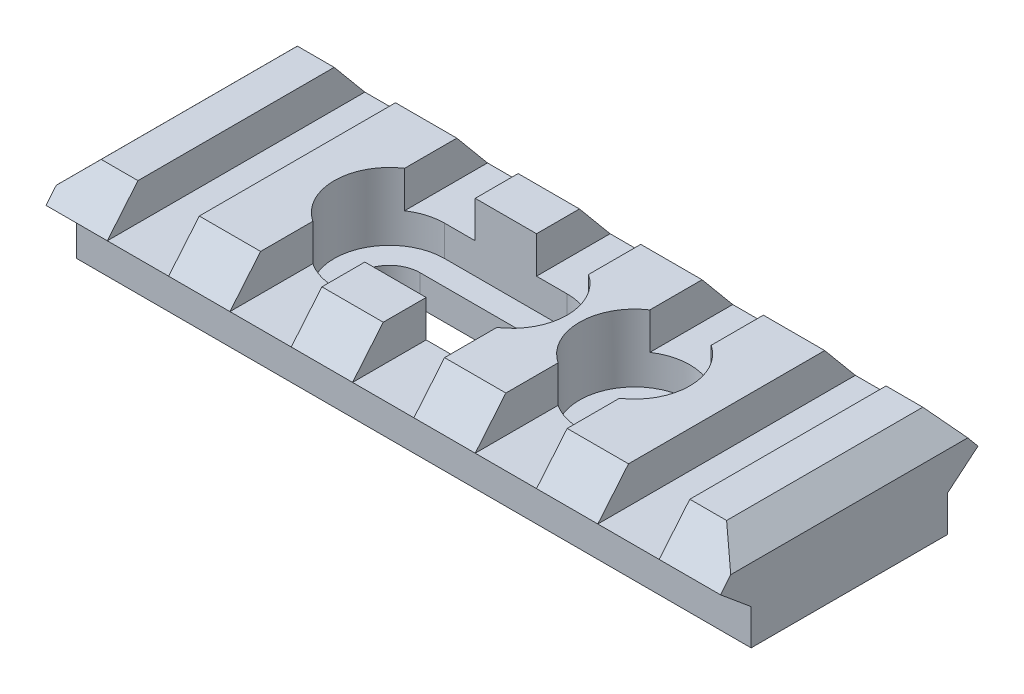
SolidWorks part; units mm, degrees
ref_plane "前视基准面" through (0, 0, 0) normal (0, 0, 1) x (1, 0, 0)
ref_plane "上视基准面" through (0, 0, 0) normal (0, 1, 0) x (1, 0, 0)
ref_plane "右视基准面" through (0, 0, 0) normal (1, 0, 0) x (0, 0, -1)
other "Configuration Table"
sketch "草图1" plane through (0, 0, 0) normal (1, 0, 0) x (0, 0, -1)
  line L0 (-8, 0) -> (8, 0)
  line L1 (8, 0) -> (8, 2.9167)
  line L2 (8, 2.9167) -> (10.5, 5)
  line L3 (10.5, 5) -> (8, 8)
  line L4 (8, 8) -> (-8, 8)
  line L5 (-8, 8) -> (-10.5, 5)
  line L6 (-10.5, 5) -> (-8, 2.9167)
  line L7 (-8, 2.9167) -> (-8, 0)
  line L8 (0, 0) -> (0, 8) construction
  dimension "D1" = 16
  dimension "D2" = 21
  dimension "D3" = 8
  dimension "D4" = 5
  dimension "D5" = 16
extrude "凸台-拉伸1" add sketch "草图1" along normal mid plane 55
sketch "草图2" plane through (0, 8, 0) normal (0, 1, 0) x (1, 0, 0)
  line L0 (27.5, 10.5) -> (-27.5, 10.5) construction
  line L1 (-2.5, -10.5) -> (2.5, -10.5)
  line L2 (-2.5, -10.5) -> (-2.5, 10.5)
  line L3 (-2.5, 10.5) -> (2.5, 10.5)
  line L4 (2.5, -10.5) -> (2.5, 10.5)
  line L5 (-2.5, -10.5) -> (2.5, 10.5) construction
  line L6 (-2.5, 10.5) -> (2.5, -10.5) construction
  point P0 (0, 0)
  dimension "D1" = 5
extrude "切除-拉伸1" cut sketch "草图2" against normal up to vertex (3 mm away) up to point (27.5, 5, 10.5)
pattern_linear "阵列(线性)1" count 3 spacing 10 along (1, 0, 0) of "切除-拉伸1"
pattern_linear "阵列(线性)2" count 3 spacing 10 along (-1, 0, 0) of "阵列(线性)1"
sketch "草图3" plane through (0, 0, 0) normal (0, -1, 0) x (1, 0, 0)
  line L0 (27.5, 8) -> (27.5, -8) construction
  line L1 (-10, 0) -> (0, 0) construction
  line L2 (-10, 2.5) -> (0, 2.5)
  line L3 (-10, -2.5) -> (0, -2.5)
  line L4 (-27.5, 8) -> (-27.5, -8) construction
  circle A0 centre (10, 0) radius 2.5
  arc A1 (-10, 2.5) -> (-10, -2.5) centre (-10, 0) ccw
  arc A2 (0, -2.5) -> (0, 2.5) centre (0, 0) ccw
  point P7 (-5, 0)
  dimension "D1" = 5
  dimension "D3" = 2.5
  dimension "D2" = 17.5
  dimension "D4" = 17.5
  dimension "D5" = 10
extrude "切除-拉伸2" cut sketch "草图3" against normal blind 55 and the other way through all
sketch "草图4" plane through (0, 0, 0) normal (0, 0, 1) x (1, 0, 0)
  line L0 (-27.5, 6.0036) -> (-25.5, 8)
  line L1 (-27.5, 8) -> (-27.5, 5) construction
  line L2 (-22.5, 8) -> (-27.5, 8) construction
  line L3 (-25.5, 8) -> (-27.5, 8)
  line L4 (-27.5, 8) -> (-27.5, 6.0036)
  dimension "D1" = 3
  dimension "D2" = 1.0036
extrude "切除-拉伸3" cut sketch "草图4" against normal through all both and the other way through all
mirror "镜向1" about plane through (0, 0, 0) normal (1, 0, 0) of "切除-拉伸3"
sketch "草图5" plane through (0, 8, 0) normal (0, 1, 0) x (1, 0, 0)
  line L0 (-10, 0) -> (0, 0) construction
  line L1 (-10, 4.5) -> (0, 4.5)
  line L2 (-10, -4.5) -> (0, -4.5)
  circle A0 centre (10, 0) radius 4.5
  arc A1 (-10, 4.5) -> (-10, -4.5) centre (-10, 0) ccw
  arc A2 (0, -4.5) -> (0, 4.5) centre (0, 0) ccw
  point P7 (-5, 0)
  dimension "D1" = 4.5
  dimension "D2" = 9
extrude "切除-拉伸4" cut sketch "草图5" against normal offset from surface (5.5 mm away) 2.5 up to face at (-5, 0, 0)
